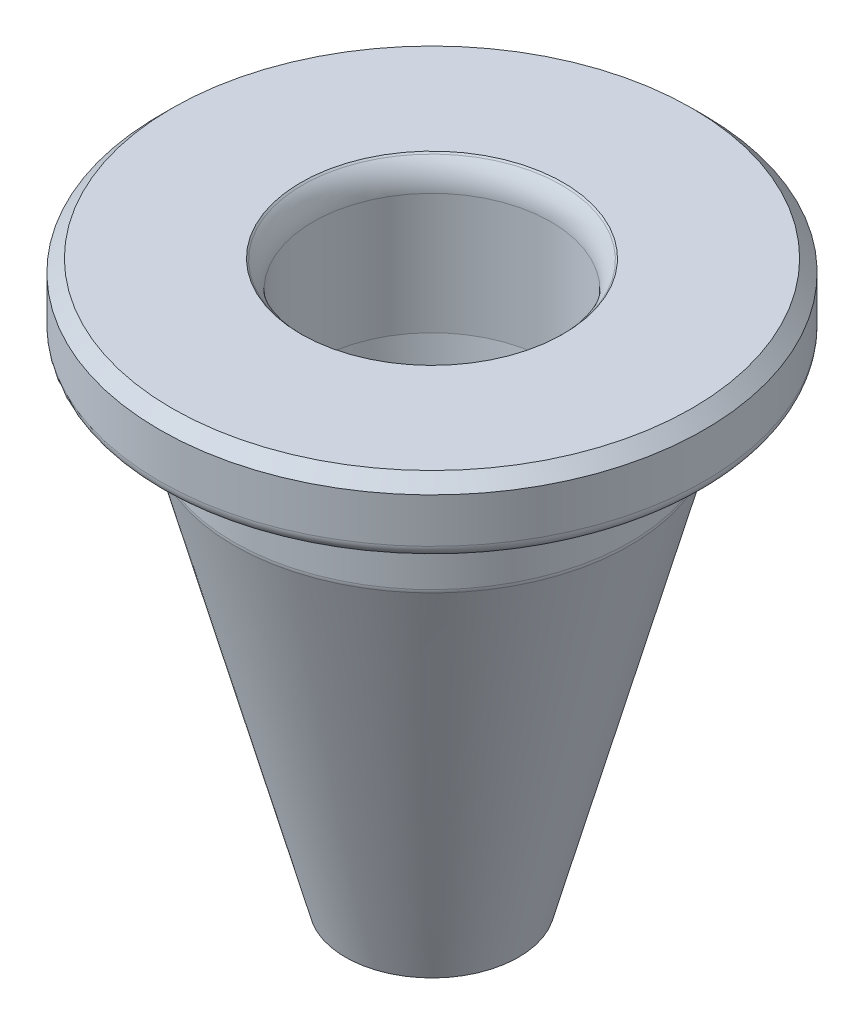
SolidWorks part; units mm, degrees
ref_plane "Ebene vorne" through (0, 0, 0) normal (0, 0, 1) x (1, 0, 0)
ref_plane "Ebene oben" through (0, 0, 0) normal (0, 1, 0) x (1, 0, 0)
ref_plane "Ebene rechts" through (0, 0, 0) normal (1, 0, 0) x (0, 0, -1)
sketch "Skizze1" plane through (0, 0, 0) normal (0, 0, 1) x (1, 0, 0)
  line L0 (0, 0) -> (0, 22) construction
  line L1 (3, 0) -> (4.8, 17)
  line L2 (4.8, 17) -> (4.8, 22)
  line L3 (4.8, 22) -> (8, 22)
  line L5 (8, 22) -> (8, 17)
  line L7 (3, 0) -> (3.5, 0.3)
  line L8 (3.5, 0.3) -> (8, 17)
  dimension "D1" = 9.6
  dimension "D2" = 22
  dimension "D3" = 5
  dimension "D4" = 6
  dimension "D5" = 16
  dimension "D6" = 0.5
  dimension "D7" = 0.3
revolve "Rotation1" add sketch "Skizze1" angle 360 about L0
other "Fläche verschieben1" face at (0, 22, -4.8) parameters "D1"=1
sketch "Skizze2" plane through (0, 23, 0) normal (0, 1, 0) x (1, 0, 0)
  circle A0 centre (0, 0) radius 4.8
  circle A1 centre (0, 0) radius 11
  dimension "D1" = 9.6
  dimension "D2" = 22
extrude "Aufsatz-Linear austragen1" add sketch "Skizze2" against normal blind 2.8
fillet "Verrundung1" radius 0.5 3 edges at (0, 20.2, 11) (0, 20.2, 8) (0, 17, -8)
ref_plane "Ebene1" through (0, 0, 0) normal (0, 0, 1) x (1, 0, 0)
chamfer "Fase1" distance 0.5 angle 45 2 edges at (0, 23, 4.8) (0, 23, 11)
fillet "Verrundung2" radius 1.5 1 edges at (0, 22.5, 4.8)
